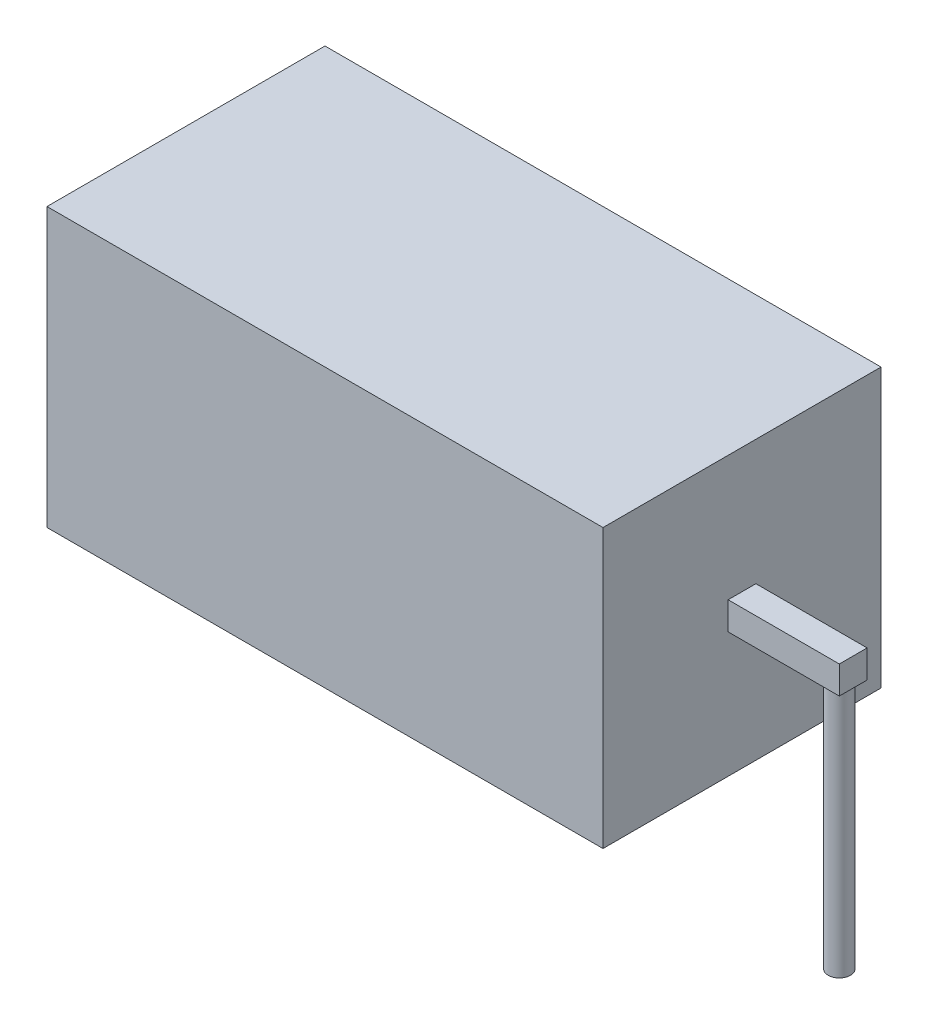
SolidWorks part; units mm, degrees
ref_plane "Спереди" through (0, 0, 0) normal (0, 0, 1) x (1, 0, 0)
ref_plane "Сверху" through (0, 0, 0) normal (0, 1, 0) x (1, 0, 0)
ref_plane "Справа" through (0, 0, 0) normal (1, 0, 0) x (0, 0, -1)
sketch "Эскиз1" plane through (0, 0, 0) normal (0, 0, 1) x (1, 0, 0)
  line L1 (0, 0) -> (20, 0)
  line L2 (0, 0) -> (0, 10)
  line L3 (0, 10) -> (20, 10)
  line L4 (20, 0) -> (20, 10)
  dimension "D1" = 10
  dimension "D2" = 20
extrude "Вытянуть1" add sketch "Эскиз1" along normal blind 10
sketch "Эскиз2" plane through (20, 0, 0) normal (1, 0, 0) x (0, 0, -1)
  line L0 (-10.8705, 5) -> (1.1033, 5) construction
  line L1 (-5, 10.8922) -> (-5, 4.5869) construction
  line L2 (-10, 10) -> (0, 10) construction
  line L3 (-10, 0) -> (0, 0) construction
  line L4 (-10, 0) -> (-10, 10) construction
  line L5 (0, 0) -> (0, 10) construction
  line L7 (-5.5, 4.5) -> (-4.5, 4.5)
  line L8 (-5.5, 4.5) -> (-5.5, 5.5)
  line L9 (-5.5, 5.5) -> (-4.5, 5.5)
  line L10 (-4.5, 4.5) -> (-4.5, 5.5)
  dimension "D1" = 1
extrude "Вытянуть2" add sketch "Эскиз2" along normal blind 4 and the other way blind 24
sketch "Эскиз3" plane through (0, 4.5, 0) normal (0, -1, 0) x (1, 0, 0)
  line L0 (-3.5, 5) -> (23.3087, 5) construction
  line L1 (0, 10) -> (20, 10) construction
  line L2 (0, 0) -> (20, 0) construction
  line L3 (10, 11.1302) -> (10, -1.0428) construction
  line L4 (0, 10) -> (0, 0) construction
  line L5 (20, 10) -> (20, 0) construction
  circle A0 centre (-3.5, 5) radius 0.4
  circle A1 centre (23.5, 5) radius 0.4
  dimension "D1" = 27
  dimension "D2" = 0.8
extrude "Вытянуть3" add sketch "Эскиз3" along normal blind 9
